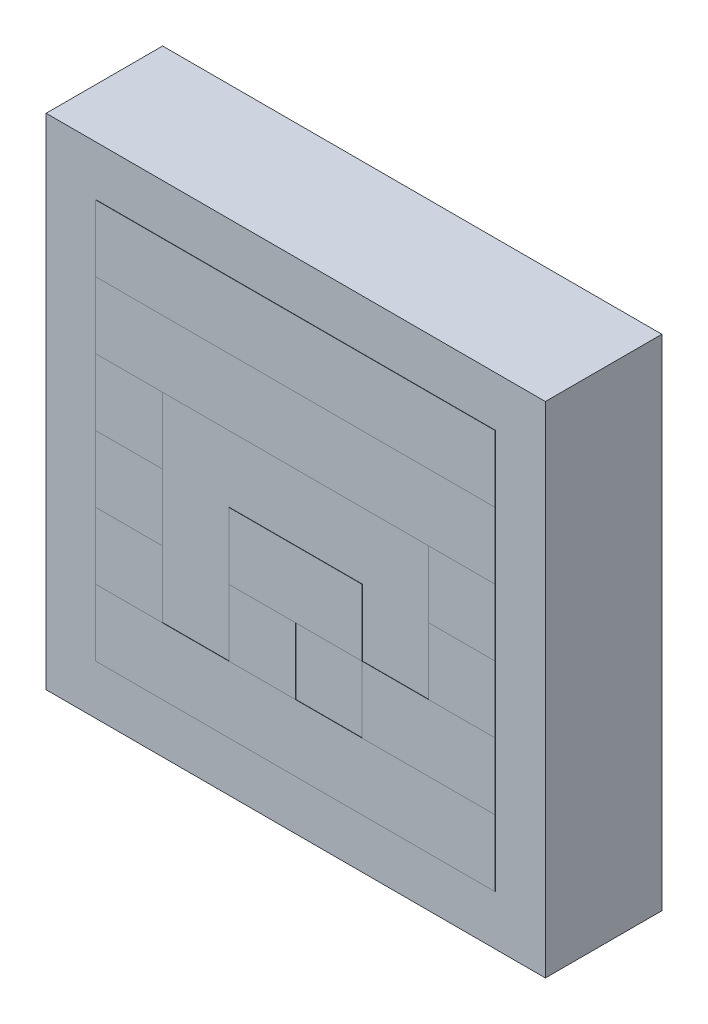
SolidWorks part; units mm, degrees
ref_plane "前视基准面" through (0, 0, 0) normal (0, 0, 1) x (1, 0, 0)
ref_plane "上视基准面" through (0, 0, 0) normal (0, 1, 0) x (1, 0, 0)
ref_plane "右视基准面" through (0, 0, 0) normal (1, 0, 0) x (0, 0, -1)
other "Configuration Table"
sketch "草图1" plane through (0, 0, 0) normal (0, 0, 1) x (1, 0, 0)
  line L1 (-30, -30) -> (30, -30)
  line L2 (-30, -30) -> (-30, 30)
  line L3 (-30, 30) -> (30, 30)
  line L4 (30, -30) -> (30, 30)
  dimension "D1" = 30
  dimension "D2" = 30
  dimension "D3" = 30
extrude "Coplanar_support60x60x14" add sketch "草图1" against normal blind 14
sketch "草图2" plane through (0, 0, 0) normal (0, 0, 1) x (1, 0, 0)
  line L1 (-24, 16) -> (24, 16)
  line L2 (-24, 16) -> (-24, 24)
  line L3 (-24, 24) -> (24, 24)
  line L4 (24, 16) -> (24, 24)
extrude "ID1_row0" add sketch "草图2" along normal blind 0.04 separate body
sketch "草图3" plane through (0, 0, 0) normal (0, 0, 1) x (1, 0, 0)
  line L1 (-24, 8) -> (24, 8)
  line L2 (-24, 8) -> (-24, 16)
  line L3 (-24, 16) -> (24, 16)
  line L4 (24, 8) -> (24, 16)
extrude "ID1_row1" add sketch "草图3" along normal blind 0.04 separate body
sketch "草图4" plane through (0, 0, 0) normal (0, 0, 1) x (1, 0, 0)
  line L1 (-24, 0) -> (-16, 0)
  line L2 (-24, 0) -> (-24, 8)
  line L3 (-24, 8) -> (-16, 8)
  line L4 (-16, 0) -> (-16, 8)
  line L6 (16, 0) -> (24, 0)
  line L7 (16, 0) -> (16, 8)
  line L8 (16, 8) -> (24, 8)
  line L9 (24, 0) -> (24, 8)
extrude "ID1_row2" add sketch "草图4" along normal blind 0.04 separate body
sketch "草图5" plane through (0, 0, 0) normal (0, 0, 1) x (1, 0, 0)
  line L1 (-24, -8) -> (-16, -8)
  line L2 (-24, -8) -> (-24, 0)
  line L3 (-24, 0) -> (-16, 0)
  line L4 (-16, -8) -> (-16, 0)
  line L6 (-8, -8) -> (8, -8)
  line L7 (-8, -8) -> (-8, 0)
  line L8 (-8, 0) -> (8, 0)
  line L9 (8, -8) -> (8, 0)
  line L11 (16, -8) -> (24, -8)
  line L12 (16, -8) -> (16, 0)
  line L13 (16, 0) -> (24, 0)
  line L14 (24, -8) -> (24, 0)
extrude "ID1_row3" add sketch "草图5" along normal blind 0.04 separate body
sketch "草图6" plane through (0, 0, 0) normal (0, 0, 1) x (1, 0, 0)
  line L1 (-24, -16) -> (-16, -16)
  line L2 (-24, -16) -> (-24, -8)
  line L3 (-24, -8) -> (-16, -8)
  line L4 (-16, -16) -> (-16, -8)
  line L6 (-8, -16) -> (0, -16)
  line L7 (-8, -16) -> (-8, -8)
  line L8 (-8, -8) -> (0, -8)
  line L9 (0, -16) -> (0, -8)
  line L11 (8, -16) -> (24, -16)
  line L12 (8, -16) -> (8, -8)
  line L13 (8, -8) -> (24, -8)
  line L14 (24, -16) -> (24, -8)
extrude "ID1_row4" add sketch "草图6" along normal blind 0.04 separate body
sketch "草图7" plane through (0, 0, 0) normal (0, 0, 1) x (1, 0, 0)
  line L1 (-24, -24) -> (24, -24)
  line L2 (-24, -24) -> (-24, -16)
  line L3 (-24, -16) -> (24, -16)
  line L4 (24, -24) -> (24, -16)
extrude "ID1_row5" add sketch "草图7" along normal blind 0.04 separate body
